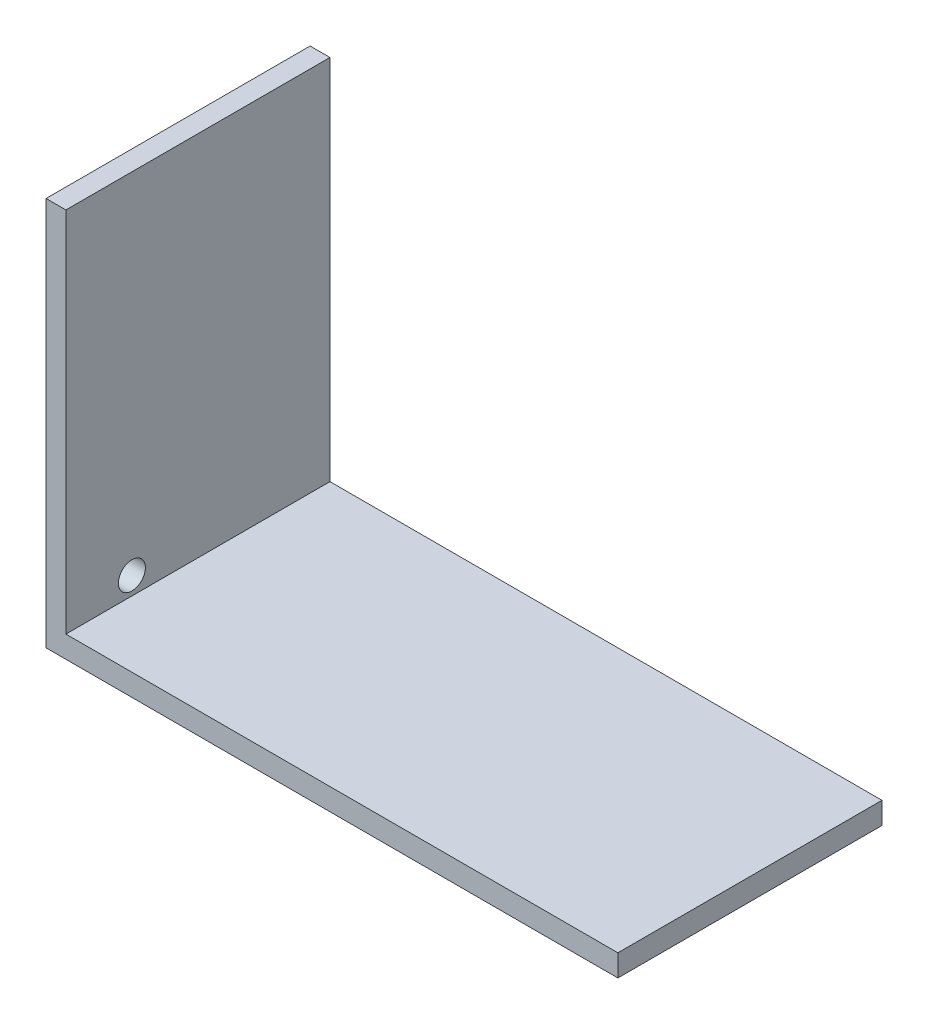
SolidWorks part; units mm, degrees
ref_plane "Front Plane" through (0, 0, 0) normal (0, 0, 1) x (1, 0, 0)
ref_plane "Top Plane" through (0, 0, 0) normal (0, 1, 0) x (1, 0, 0)
ref_plane "Right Plane" through (0, 0, 0) normal (1, 0, 0) x (0, 0, -1)
sketch "Sketch1" plane through (0, 0, 0) normal (0, 1, 0) x (1, 0, 0)
  line L5 (-3.675, 30.75) -> (65.825, 30.75)
  line L6 (65.825, -2.5) -> (65.825, 30.75)
  line L7 (-3.675, -2.5) -> (65.825, -2.5)
  line L16 (-3.675, -2.5) -> (-3.675, 30.75)
  line L17 (65.825, -1.125) -> (65.825, 29.375) construction
  dimension "D2" = 33.25
  dimension "D3" = 69.5
  dimension "D1" = 2.5
extrude "Boss-Extrude1" add sketch "Sketch1" along normal blind 2.75
sketch "Sketch2" plane through (-3.675, 0, 0) normal (-1, 0, 0) x (0, 0, 1)
  line L0 (2.5, 2.75) -> (2.5, 0) construction
  line L1 (-30.75, 0) -> (2.5, 0)
  line L2 (-30.75, 0) -> (-30.75, 49)
  line L3 (-30.75, 49) -> (2.5, 49)
  line L4 (2.5, 0) -> (2.5, 49)
  dimension "D1" = 49
extrude "Boss-Extrude2" add sketch "Sketch2" along normal blind 2.5
hole_wizard "M3 Clearance Hole1" positions "Sketch6" profile "Sketch4" hole size "M3" standard "ANSI Metric" end condition up to next
sketch "Sketch6" plane through (-6.175, 0, 0) normal (-1, 0, 0) x (0, 0, 1)
  line L0 (2.5, 5) -> (-14.125, 5) construction
  line L1 (2.5, 0) -> (2.5, 49) construction
  line L3 (-30.75, 0) -> (2.5, 0) construction
  point P9 (-14.125, 0)
  point P10 (-5.8125, 5)
  dimension "D1" = 5
sketch "Sketch4" plane through (-6.175, 5, -5.8125) normal (0, 1, 0) x (0, 0, 1)
  line L0 (0, 0) -> (0, 2.5)
  line L1 (0, 2.5) -> (1.7, 2.5)
  line L2 (1.7, 2.5) -> (1.7, 0)
  line L5 (1.7, 0) -> (0, 0)
  line L11 (0, -6.35) -> (0, 107.95) construction
  dimension "Thru Hole Dia." = 3.4
  dimension "Thru Hole Depth" = 2.5
